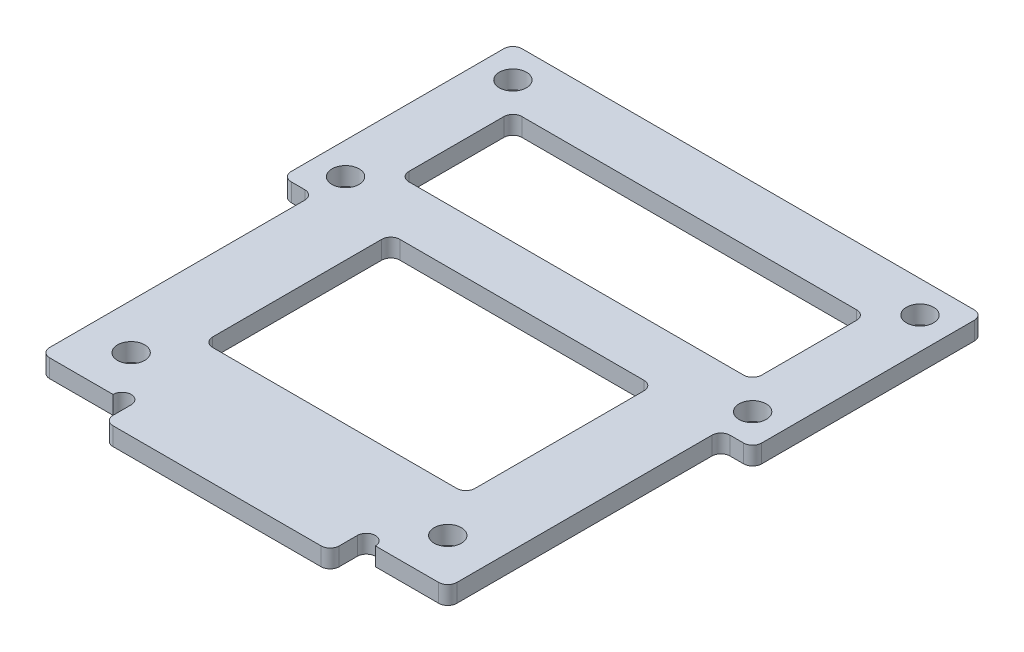
SolidWorks part; units mm, degrees
material "Thornel Mat VMA"
ref_plane "前视基准面" through (0, 0, 0) normal (0, 0, 1) x (1, 0, 0)
ref_plane "上视基准面" through (0, 0, 0) normal (0, 1, 0) x (1, 0, 0)
ref_plane "右视基准面" through (0, 0, 0) normal (1, 0, 0) x (0, 0, -1)
sketch "草图1" plane through (0, 0, 0) normal (0, 1, 0) x (1, 0, 0)
  line L0 (0, -1.1) -> (0, 1.1) construction
  line L2 (-22.5, 3) -> (-22.5, 33.2)
  line L3 (-26, 58.7) -> (26, 58.7)
  line L4 (22.5, 3) -> (22.5, 33.2)
  line L5 (-22.5, 55.2) -> (22.5, 55.2) construction
  line L6 (-22.5, 55.2) -> (-22.5, 36.7) construction
  line L7 (-22.5, 36.7) -> (22.5, 36.7) construction
  line L8 (22.5, 55.2) -> (22.5, 36.7) construction
  line L10 (-12.5, 0) -> (-12.5, 3)
  line L11 (-12.5, 3) -> (-22.5, 3)
  line L14 (12.5, 3) -> (22.5, 3)
  line L15 (12.5, 0) -> (12.5, 3)
  line L17 (-12.5, 0) -> (12.5, 0)
  line L19 (-19.5, 52.2) -> (19.5, 52.2)
  line L20 (19.5, 52.2) -> (19.5, 39.7)
  line L21 (-19.5, 39.7) -> (19.5, 39.7)
  line L22 (-19.5, 52.2) -> (-19.5, 39.7)
  line L23 (26, 33.2) -> (22.5, 33.2)
  line L25 (26, 33.2) -> (26, 58.7)
  line L26 (-26, 33.2) -> (-22.5, 33.2)
  line L28 (-26, 33.2) -> (-26, 58.7)
  circle A0 centre (-22.5, 55.2) radius 1.5
  circle A1 centre (-22.5, 36.7) radius 1.5
  circle A2 centre (22.5, 36.7) radius 1.5
  circle A3 centre (22.5, 55.2) radius 1.5
  circle A4 centre (-17.5, 8) radius 1.5
  circle A5 centre (17.5, 8) radius 1.5
  dimension "D5" = 3
  dimension "D6" = 3.5
  dimension "D10" = 3
  dimension "D11" = 3.5
  dimension "D12" = 3.5
  dimension "D3" = 5
  dimension "D4" = 5
  dimension "D1" = 18.5
  dimension "D2" = 45
  dimension "D7" = 3
  dimension "D8" = 33.7
  dimension "D9" = 25
  dimension "D14" = 10
  dimension "D13" = 3
extrude "凸台-拉伸1" add sketch "草图1" along normal blind 2
sketch "草图2" plane through (0, 2, 0) normal (0, 1, 0) x (1, 0, 0)
  line L2 (0, -1.1) -> (0, 1.1) construction
  line L3 (-22.5, 3) -> (-12.5, 3) construction
  line L4 (-14.5, 33.7) -> (14.5, 33.7)
  line L5 (-14.5, 33.7) -> (-14.5, 13)
  line L6 (-14.5, 13) -> (14.5, 13)
  line L7 (14.5, 33.7) -> (14.5, 13)
  line L9 (-19.5, 39.7) -> (19.5, 39.7) construction
  line L10 (-22.5, 33.2) -> (-22.5, 3) construction
  line L11 (22.5, 3) -> (22.5, 33.2) construction
  circle A1 centre (-13.5, 3) radius 1
  circle A2 centre (13.5, 3) radius 1
  dimension "D1" = 2
  dimension "D2" = 6
  dimension "D3" = 8
  dimension "D4" = 8
  dimension "D5" = 10
extrude "切除-拉伸1" cut sketch "草图2" against normal through all
fillet "圆角1" radius 1 18 edges at (-19.5, 1, -39.7) (19.5, 1, -39.7) (19.5, 1, -52.2) (14.5, 1, -13) (14.5, 1, -33.7) (-14.5, 1, -33.7) (-14.5, 1, -13) (-19.5, 1, -52.2) (22.5, 1, -3) (-22.5, 1, -3) (12.5, 1, 0) (-12.5, 1, 0) (-26, 1, -58.7) (26, 1, -58.7) (26, 1, -33.2) (22.5, 1, -33.2) (-22.5, 1, -33.2) (-26, 1, -33.2)
